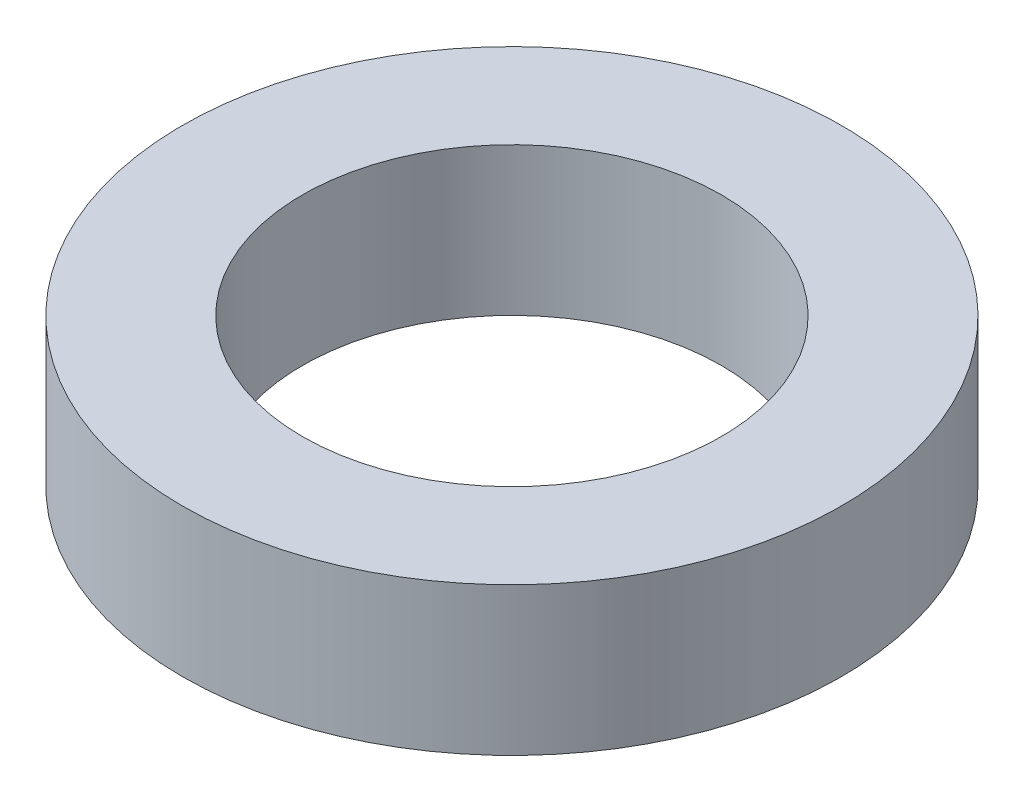
SolidWorks part; units mm, degrees
ref_plane "Front Plane" through (0, 0, 0) normal (0, 0, 1) x (1, 0, 0)
ref_plane "Top Plane" through (0, 0, 0) normal (0, 1, 0) x (1, 0, 0)
ref_plane "Right Plane" through (0, 0, 0) normal (1, 0, 0) x (0, 0, -1)
sketch "Sketch1" plane through (0, 0, 0) normal (0, 1, 0) x (1, 0, 0)
  circle A0 centre (0, 0) radius 3.4
  circle A1 centre (0, 0) radius 5.35
  dimension "D1" = 6.8
  dimension "D2" = 1.95
extrude "Boss-Extrude1" add sketch "Sketch1" along normal blind 2.4
